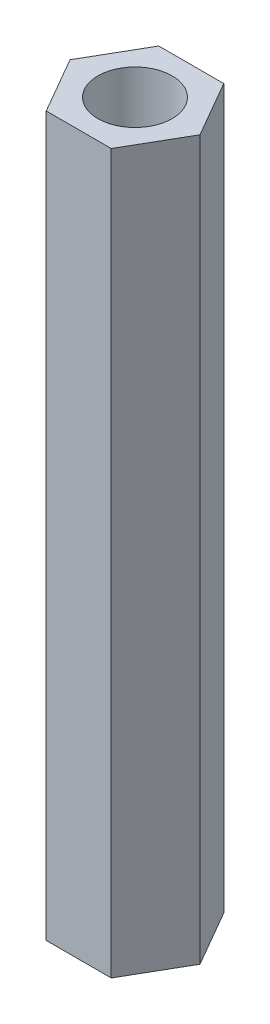
SolidWorks part; units mm, degrees
material "黄铜"
ref_plane "前视基准面" through (0, 0, 0) normal (0, 0, 1) x (1, 0, 0)
ref_plane "上视基准面" through (0, 0, 0) normal (0, 1, 0) x (1, 0, 0)
ref_plane "右视基准面" through (0, 0, 0) normal (1, 0, 0) x (0, 0, -1)
sketch "草图1" plane through (0, 0, 0) normal (0, 1, 0) x (1, 0, 0)
  line L1 (2.7135, 0) -> (1.3568, 2.35)
  line L2 (1.3568, 2.35) -> (-1.3568, 2.35)
  line L3 (-1.3568, 2.35) -> (-2.7135, 0)
  line L4 (-2.7135, 0) -> (-1.3568, -2.35)
  line L5 (-1.3568, -2.35) -> (1.3568, -2.35)
  line L6 (1.3568, -2.35) -> (2.7135, 0)
  circle A0 centre (0, 0) radius 1.55
  circle A1 centre (0, 0) radius 2.35 construction
  dimension "D1" = 3.1
  dimension "D2" = 4.7
extrude "凸台-拉伸1" add sketch "草图1" along normal blind 30
